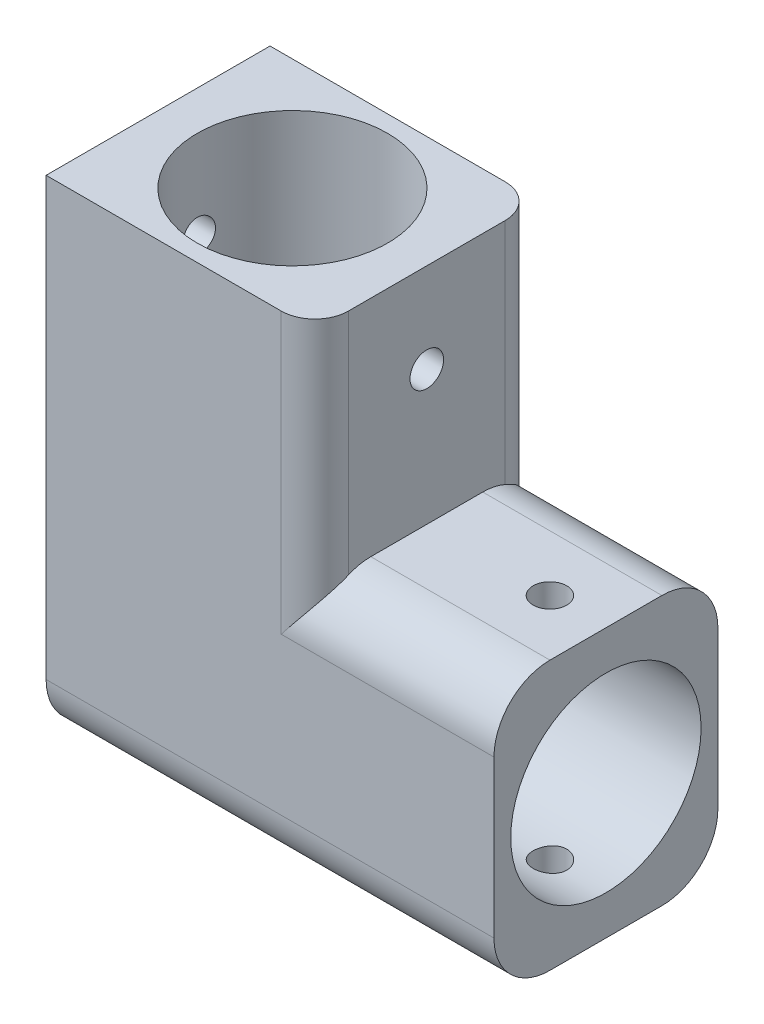
SolidWorks part; units mm, degrees
ref_plane "Alzado" through (0, 0, 0) normal (0, 0, 1) x (1, 0, 0)
ref_plane "Planta" through (0, 0, 0) normal (0, 1, 0) x (1, 0, 0)
ref_plane "Vista lateral" through (0, 0, 0) normal (1, 0, 0) x (0, 0, -1)
sketch "Croquis1" plane through (0, 0, 0) normal (0, 0, 1) x (1, 0, 0)
  line L0 (0, -19.3422) -> (0, 35.9206) construction
  line L1 (-20, -12) -> (20, -12)
  line L2 (-20, -12) -> (-20, 12)
  line L3 (-20, 12) -> (20, 12)
  line L4 (20, -12) -> (20, 12)
  line L5 (-20, -12) -> (20, 12) construction
  line L6 (-20, 12) -> (20, -12) construction
  line L7 (-20, 12) -> (4, 12)
  line L8 (-20, 12) -> (-20, 32)
  line L9 (-20, 32) -> (4, 32)
  line L10 (4, 12) -> (4, 32)
  point P0 (0, 0)
  dimension "D1" = 40
  dimension "D2" = 24
  dimension "D3" = 20
  dimension "D4" = 24
extrude "Saliente-Extruir1" add sketch "Croquis1" along normal mid plane 20 contours L1 L4 L3 L2 | L3 L10 L9 L8
sketch "Croquis3" plane through (20, 0, 0) normal (1, 0, 0) x (0, 0, -1)
  circle A0 centre (0, 0) radius 8.5
  dimension "D1" = 17
extrude "Cortar-Extruir1" cut sketch "Croquis3" against normal blind 70
sketch "Croquis4" plane through (0, 32, 0) normal (0, 1, 0) x (1, 0, 0)
  line L0 (-8, 10) -> (-8, -10) construction
  line L1 (-20, 10) -> (4, 10) construction
  line L2 (-20, -10) -> (4, -10) construction
  line L3 (4, 0) -> (-20, 0) construction
  line L4 (4, -10) -> (4, 10) construction
  line L5 (-20, -10) -> (-20, 10) construction
  circle A0 centre (-8, 0) radius 8.5
  point P15 (-3.7648, 0)
  point P16 (-9, 0)
  dimension "D1" = 17
extrude "Cortar-Extruir2" cut sketch "Croquis4" against normal blind 18
sketch "Croquis5" plane through (0, -12, 0) normal (0, -1, 0) x (1, 0, 0)
  line L0 (0, 0) -> (-15, 0) construction
  line L1 (-20, 10) -> (-20, -10) construction
  line L2 (0, 13.4644) -> (0, -14.0484) construction
  circle A0 centre (-15, 0) radius 1.5
  circle A1 centre (15, 0) radius 1.5
  dimension "D1" = 3
  dimension "D2" = 5
extrude "Cortar-Extruir3" cut sketch "Croquis5" against normal blind 25
sketch "Croquis6" plane through (-20, 0, 0) normal (-1, 0, 0) x (0, 0, 1)
  line L0 (-10, 24) -> (10, 24) construction
  line L3 (10, 32) -> (-10, 32) construction
  line L4 (0, 32) -> (0, 21.055) construction
  circle A0 centre (0, 24) radius 1.5
  dimension "D1" = 3
  dimension "D2" = 8
extrude "Cortar-Extruir4" cut sketch "Croquis6" against normal blind 30
fillet "Redondeo1" radius 5 4 edges at (12, 12, -10) (12, 12, 10) (0, -12, -10) (0, -12, 10)
fillet "Redondeo2" radius 3 2 edges at (4, 19.5, -10) (4, 19.5, 10)
